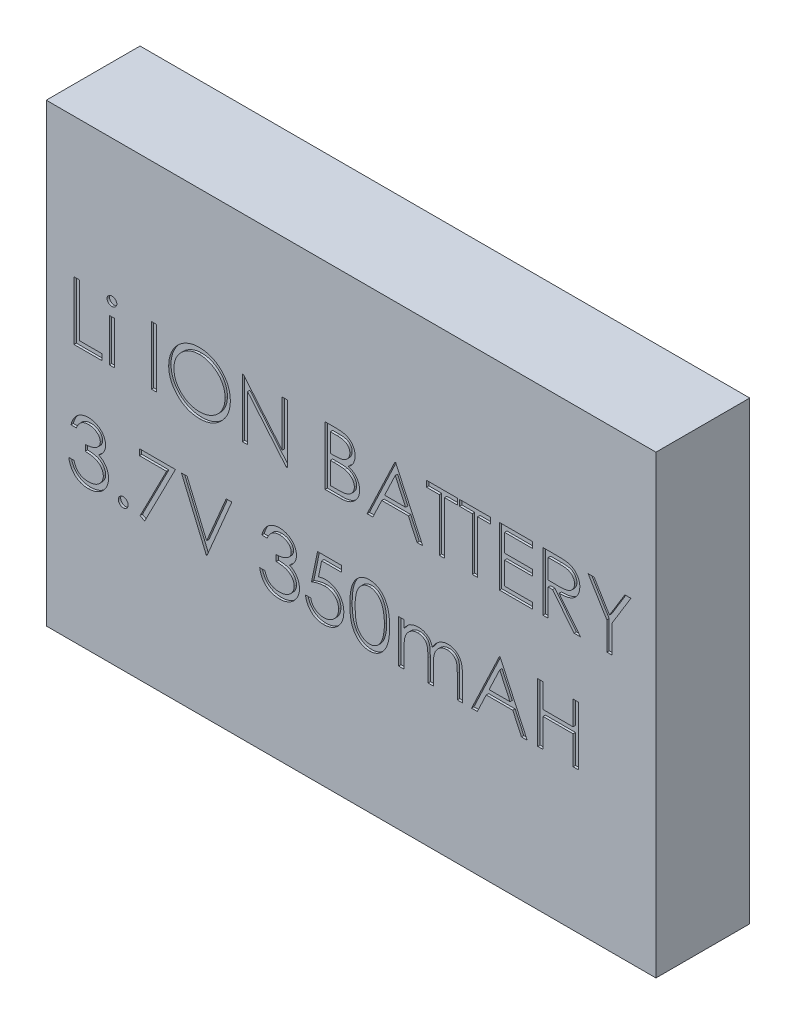
SolidWorks part; units mm, degrees
ref_plane "Front Plane" through (0, 0, 0) normal (0, 0, 1) x (1, 0, 0)
ref_plane "Top Plane" through (0, 0, 0) normal (0, 1, 0) x (1, 0, 0)
ref_plane "Right Plane" through (0, 0, 0) normal (1, 0, 0) x (0, 0, -1)
sketch "Sketch1" plane through (0, 0, 0) normal (0, 0, 1) x (1, 0, 0)
  line L1 (-16.51, -12.3317) -> (16.51, -12.3317)
  line L2 (-16.51, -12.3317) -> (-16.51, 12.3317)
  line L3 (-16.51, 12.3317) -> (16.51, 12.3317)
  line L4 (16.51, -12.3317) -> (16.51, 12.3317)
  line L5 (-16.51, -12.3317) -> (16.51, 12.3317) construction
  line L6 (-16.51, 12.3317) -> (16.51, -12.3317) construction
  point P0 (0, 0)
  dimension "D1" = 33.02
  dimension "D2" = 24.6634
extrude "Boss-Extrude1" add sketch "Sketch1" along normal mid plane 5.08
sketch "Sketch2" plane through (0, 0, 2.54) normal (0, 0, 1) x (1, 0, 0)
  line L0 (-15.4149, 0) -> (12.0038, 0) construction
  text T0 "Li ION BATTERY\r\n3.7V 350mAH"
extrude "Cut-Extrude1" cut sketch "Sketch2" against normal blind 0.127
